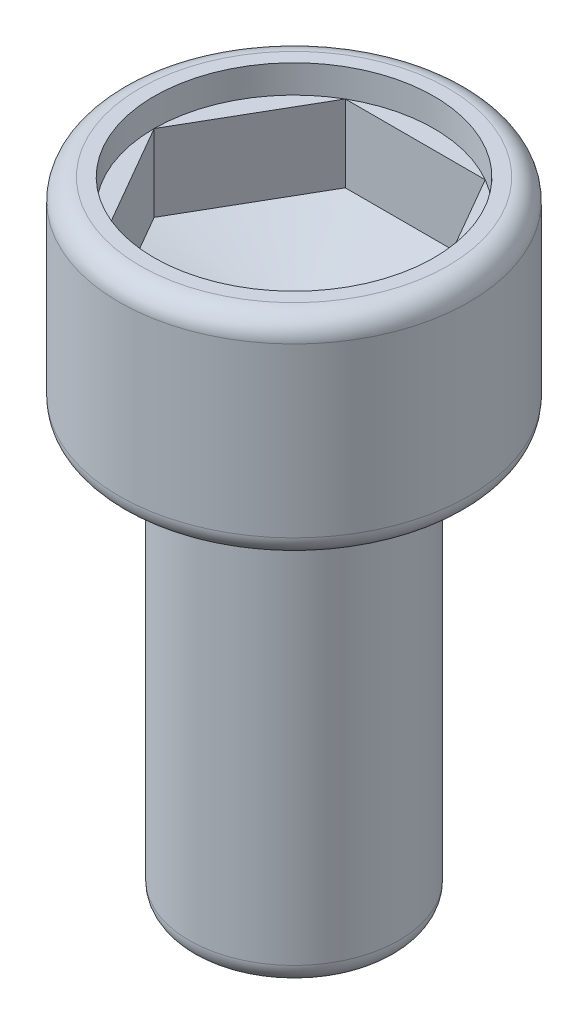
SolidWorks part; units mm, degrees
ref_plane "Front Plane" through (0, 0, 0) normal (0, 0, 1) x (1, 0, 0)
ref_plane "Top Plane" through (0, 0, 0) normal (0, 1, 0) x (1, 0, 0)
ref_plane "Right Plane" through (0, 0, 0) normal (1, 0, 0) x (0, 0, -1)
sketch "Sketch1" plane through (0, 0, 0) normal (0, 1, 0) x (1, 0, 0)
  circle A0 centre (0, 0) radius 2.5
  dimension "D1" = 5
extrude "Boss-Extrude1" add sketch "Sketch1" along normal blind 3
sketch "Sketch2" plane through (0, 3, 0) normal (0, 1, 0) x (1, 0, 0)
  line L1 (2, 0) -> (1, 1.7321)
  line L2 (1, 1.7321) -> (-1, 1.7321)
  line L3 (-1, 1.7321) -> (-2, 0)
  line L4 (-2, 0) -> (-1, -1.7321)
  line L5 (-1, -1.7321) -> (1, -1.7321)
  line L6 (1, -1.7321) -> (2, 0)
  circle A0 centre (0, 0) radius 2 construction
  dimension "D1" = 4
extrude "Cut-Extrude1" cut sketch "Sketch2" against normal blind 1.5
sketch "Sketch5" plane through (0, 1.5, 0) normal (0, 1, 0) x (1, 0, 0)
  circle A0 centre (0, 0) radius 2
extrude "Cut-Extrude2" cut sketch "Sketch5" against normal blind 0.4 from offset 1.5
sketch "Sketch6" plane through (0, 1.5, 0) normal (0, 1, 0) x (1, 0, 0)
  circle A0 centre (0, 0) radius 2
extrude "Cut-Extrude3" cut sketch "Sketch6" against normal blind 0.5 draft 76
sketch "Sketch7" plane through (0, 0, 0) normal (0, -1, 0) x (1, 0, 0)
  circle A0 centre (0, 0) radius 1.5
  dimension "D1" = 3
extrude "Boss-Extrude2" add sketch "Sketch7" along normal blind 6
fillet "Fillet1" radius 0.3 2 edges at (0, 0, 2.5) (0, 3, 2.5)
fillet "Fillet2" radius 0.3 1 edges at (0, -6, -1.5)
